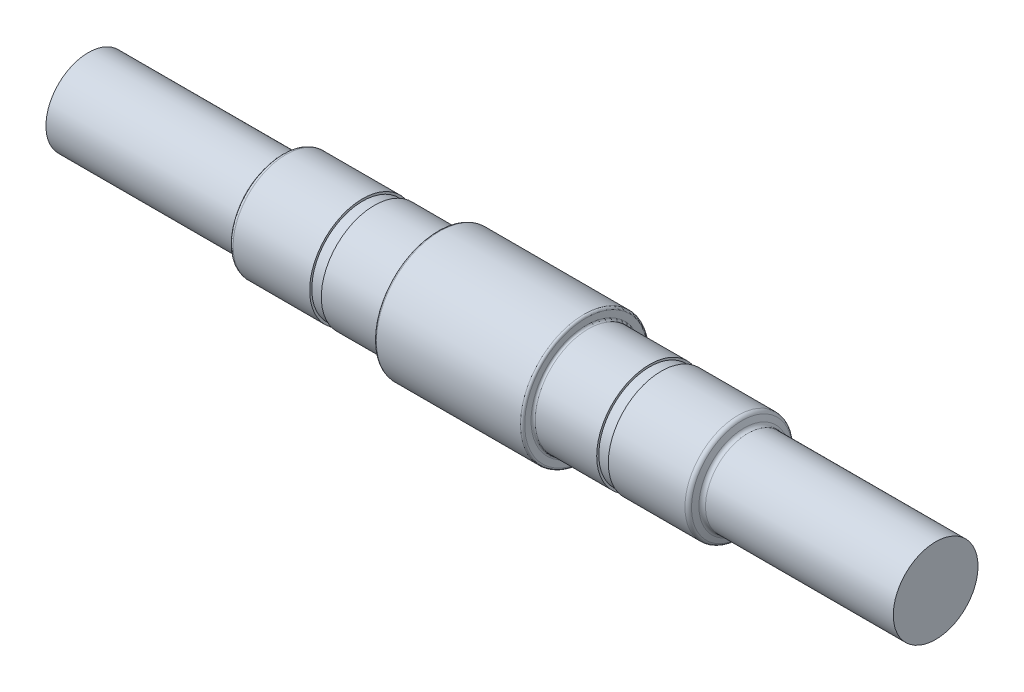
SolidWorks part; units mm, degrees
material "Plain Carbon Steel"
ref_plane "Front" through (0, 0, 0) normal (0, 0, 1) x (1, 0, 0)
ref_plane "Top" through (0, 0, 0) normal (0, 1, 0) x (1, 0, 0)
ref_plane "Right" through (0, 0, 0) normal (1, 0, 0) x (0, 0, -1)
sketch "Sketch1" plane through (0, 0, 0) normal (1, 0, 0) x (0, 0, -1)
  circle A0 centre (0, 0) radius 4
  dimension "D1" = 8
extrude "Boss-Extrude1" add sketch "Sketch1" along normal blind 40
cosmetic thread "Cosmetic Thread1" parameters "D1"=8, "D2"=7
sketch "Sketch2" plane through (0, 0, 0) normal (1, 0, 0) x (0, 0, -1)
  circle A0 centre (0, 0) radius 6
  dimension "D1" = 12
extrude "Boss-Extrude2" add sketch "Sketch2" along normal blind 7
sketch "Sketch3" plane through (0, 0, 0) normal (1, 0, 0) x (0, 0, -1)
  circle A0 centre (0, 0) radius 5
  dimension "D1" = 10
extrude "Boss-Extrude3" add sketch "Sketch3" along normal blind 21.6
fillet "Fillet1" radius 0.2 2 edges at (7, 0, -6) (7, 0, -5)
ref_plane "Plane1" through (13, 0, 0) normal (1, 0, 0) x (0, 0, -1)
sketch "Sketch4" plane through (13, 0, 0) normal (1, 0, 0) x (0, 0, -1)
  circle A0 centre (0, 0) radius 4.8
  circle A1 centre (0, 0) radius 8.0777
  dimension "D1" = 9.6
extrude "Cut-Extrude1" cut sketch "Sketch4" along normal blind 1.1
sketch "Sketch5" plane through (0, 0, 0) normal (0, 0, 1) x (1, 0, 0)
  line L0 (21.6, 5) -> (21.6, 4)
  line L1 (21.6, 4) -> (22.004, 4)
  line L2 (40, 4) -> (21.6, 4) construction
  line L3 (22.004, 4) -> (21.6, 5)
  dimension "D1" = 68
ref_axis "Axis1" through (21.6, 0, 0) along (-1, 0, 0)
revolve "Revolve1" add sketch "Sketch5" angle 360 about axis through (21.6, 0, 0) along (-1, 0, 0)
fillet "Fillet3" radius 0.4 2 edges at (22.004, 0, -4) (21.6, 0, -5)
mirror "Mirror1" about plane through (0, 0, 0) normal (1, 0, 0) of "Revolve1", "Fillet1", "Boss-Extrude3", "Boss-Extrude1", "Boss-Extrude2", "Cut-Extrude1", "Fillet3"
ref_plane "Plane2" through (0, 0, 0) normal (1, 0, 0) x (0, 0, -1)
